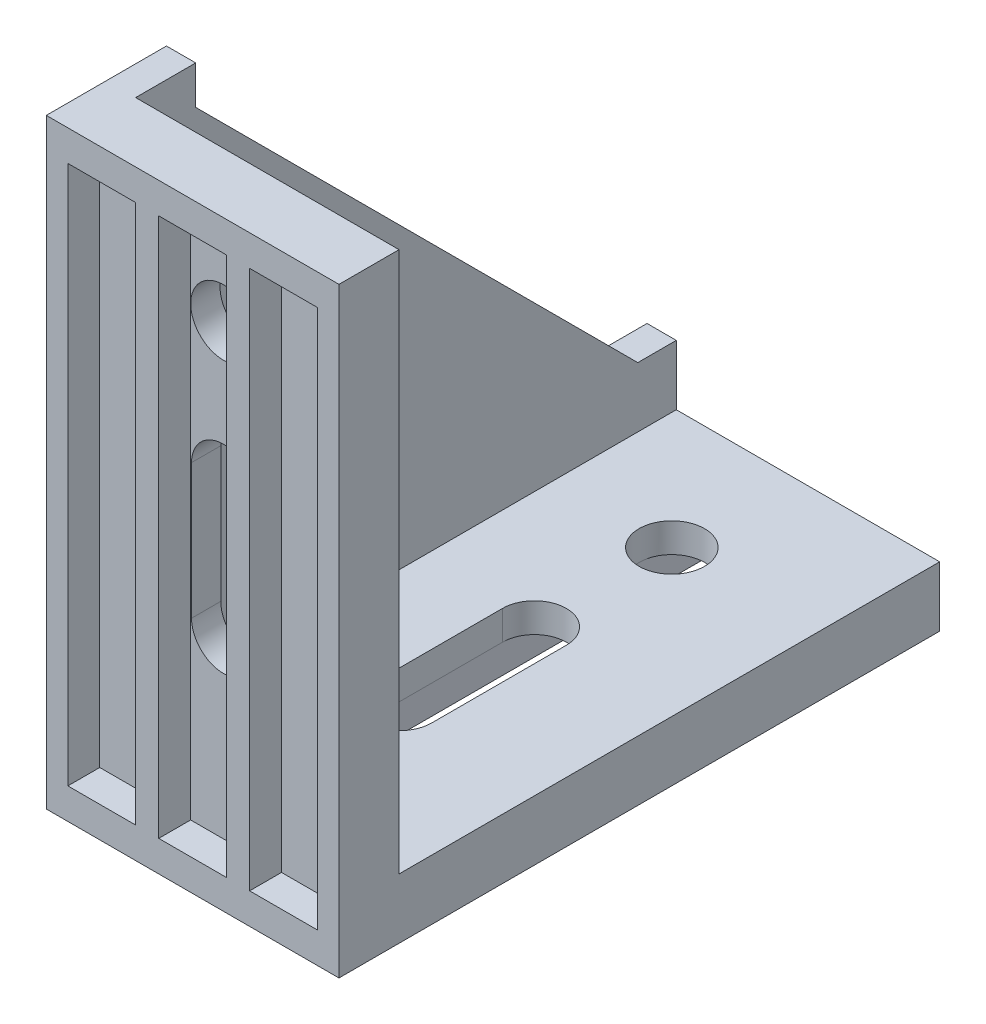
SolidWorks part; units mm, degrees
ref_plane "前视基准面" through (0, 0, 0) normal (0, 0, 1) x (1, 0, 0)
ref_plane "上视基准面" through (0, 0, 0) normal (0, 1, 0) x (1, 0, 0)
ref_plane "右视基准面" through (0, 0, 0) normal (1, 0, 0) x (0, 0, -1)
sketch "草图1" plane through (0, 0, 0) normal (0, 0, 1) x (1, 0, 0)
  line L1 (-19, 39) -> (19, 39)
  line L2 (-19, 39) -> (-19, -39)
  line L3 (-19, -39) -> (19, -39)
  line L4 (19, 39) -> (19, -39)
  line L5 (-19, 39) -> (19, -39) construction
  line L6 (-19, -39) -> (19, 39) construction
  point P0 (0, 0)
  dimension "D1" = 38
  dimension "D2" = 78
extrude "凸台-拉伸1" add sketch "草图1" along normal blind 7.8
sketch "草图3" plane through (0, 0, 7.8) normal (0, 0, 1) x (1, 0, 0)
  line L0 (19, -39) -> (19, 39) construction
  line L1 (-19, -39) -> (19, -39)
  line L2 (-19, -39) -> (-19, -31.2)
  line L3 (-19, -31.2) -> (19, -31.2)
  line L4 (19, -39) -> (19, -31.2)
  dimension "D1" = 7.8
extrude "凸台-拉伸2" add sketch "草图3" against normal blind 78
sketch "草图4" plane through (-19, 0, 0) normal (-1, 0, 0) x (0, 0, 1)
  line L0 (0, 39) -> (-7.8, 39)
  line L1 (-7.8, 39) -> (-7.8, 34)
  line L2 (-7.8, 34) -> (-65.2, -23.4)
  line L3 (-65.2, -23.4) -> (-70.2, -23.4)
  line L4 (-70.2, -23.4) -> (-70.2, -31.2)
  line L5 (-70.2, -31.2) -> (0, -31.2)
  line L6 (0, -31.2) -> (0, 39)
  dimension "D1" = 7.8
  dimension "D2" = 5
  dimension "D3" = 7.8
  dimension "D4" = 5
extrude "凸台-拉伸3" add sketch "草图4" against normal blind 3.8
sketch "草图5" plane through (0, -31.2, 0) normal (0, 1, 0) x (1, 0, 0)
  line L0 (0, 19.0832) -> (0, 36.5832) construction
  line L1 (-4.1431, 19.0832) -> (-4.1431, 36.5832)
  line L2 (4.1431, 19.0832) -> (4.1431, 36.5832)
  circle A0 centre (0, 54.4165) radius 4.25
  arc A1 (-4.1431, 19.0832) -> (4.1431, 19.0832) centre (0, 19.0832) ccw
  arc A2 (4.1431, 36.5832) -> (-4.1431, 36.5832) centre (0, 36.5832) ccw
  point P5 (0, 27.8332)
  dimension "D1" = 8.5
  dimension "D2" = 17.5
extrude "切除-拉伸1" cut sketch "草图5" against normal through all
ref_plane "基准面1" through (0, -15.6, -15.6) normal (0, 0.7071, 0.7071) x (1, 0, 0)
mirror "镜向1" about plane through (0, -15.6, -15.6) normal (0, 0.7071, 0.7071) of "切除-拉伸1"
sketch "草图6" plane through (0, -39, 0) normal (0, -1, 0) x (1, 0, 0)
  line L0 (19, 7.8) -> (19, -70.2) construction
  line L1 (-16.2, 3.8) -> (-7.4, 3.8)
  line L2 (-16.2, 3.8) -> (-16.2, -66.2)
  line L3 (-16.2, -66.2) -> (-7.4, -66.2)
  line L4 (-7.4, 3.8) -> (-7.4, -66.2)
  line L5 (-4.4, 3.8) -> (4.4, 3.8)
  line L6 (-4.4, 3.8) -> (-4.4, -66.2)
  line L7 (-4.4, -66.2) -> (4.4, -66.2)
  line L8 (4.4, 3.8) -> (4.4, -66.2)
  line L9 (7.4, 3.8) -> (16.2, 3.8)
  line L10 (7.4, 3.8) -> (7.4, -66.2)
  line L11 (7.4, -66.2) -> (16.2, -66.2)
  line L12 (16.2, 3.8) -> (16.2, -66.2)
  line L13 (-19, 7.8) -> (-19, -70.2) construction
  line L14 (-19, -70.2) -> (19, -70.2) construction
  line L15 (-19, 7.8) -> (19, 7.8) construction
  dimension "D1" = 2.8
  dimension "D2" = 3
  dimension "D3" = 3
  dimension "D4" = 2.8
  dimension "D5" = 4
  dimension "D6" = 4
extrude "切除-拉伸2" cut sketch "草图6" against normal blind 4 draft 2
sketch "草图7" plane through (0, 0, 7.8) normal (0, 0, 1) x (1, 0, 0)
  line L0 (-19, 39) -> (-19, -39) construction
  line L1 (-4.4, 35) -> (4.4, 35)
  line L2 (-4.4, 35) -> (-4.4, -35)
  line L3 (-4.4, -35) -> (4.4, -35)
  line L4 (4.4, 35) -> (4.4, -35)
  line L5 (-16.2, 35) -> (-7.4, 35)
  line L6 (-16.2, 35) -> (-16.2, -35)
  line L7 (-16.2, -35) -> (-7.4, -35)
  line L8 (-7.4, 35) -> (-7.4, -35)
  line L9 (7.4, 35) -> (16.2, 35)
  line L10 (7.4, 35) -> (7.4, -35)
  line L11 (7.4, -35) -> (16.2, -35)
  line L12 (16.2, 35) -> (16.2, -35)
  line L13 (19, -39) -> (19, 39) construction
  line L14 (-19, -39) -> (19, -39) construction
  line L15 (19, 39) -> (-19, 39) construction
  dimension "D1" = 2.8
  dimension "D2" = 3
  dimension "D3" = 3
  dimension "D4" = 2.8
  dimension "D5" = 4
  dimension "D6" = 4
extrude "切除-拉伸3" cut sketch "草图7" against normal blind 4 draft 2
